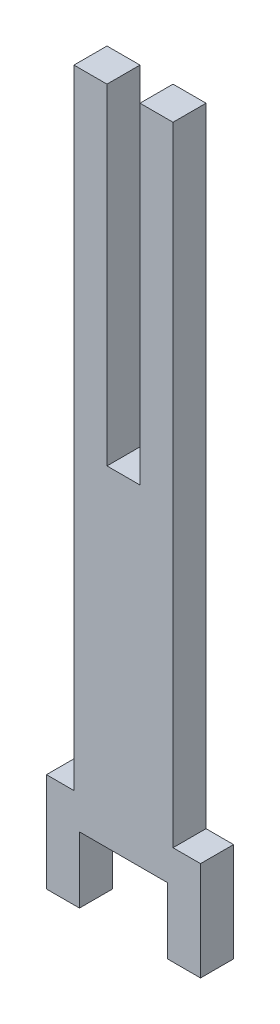
SolidWorks part; units mm, degrees
ref_plane "Front Plane" through (0, 0, 0) normal (0, 0, 1) x (1, 0, 0)
ref_plane "Top Plane" through (0, 0, 0) normal (0, 1, 0) x (1, 0, 0)
ref_plane "Right Plane" through (0, 0, 0) normal (1, 0, 0) x (0, 0, -1)
sketch "스케치1" plane through (0, 0, 0) normal (0, 0, 1) x (1, 0, 0)
  line L0 (0, 0) -> (0, -27.044) construction
  line L1 (-7, -33.044) -> (7, -33.044) construction
  line L2 (-7, -33.044) -> (-7, 33.044) construction
  line L3 (-7, 33.044) -> (7, 33.044) construction
  line L4 (7, -33.044) -> (7, 33.044) construction
  line L5 (-7, -33.044) -> (7, 33.044) construction
  line L6 (-7, 33.044) -> (7, -33.044) construction
  line L7 (-4, -33.044) -> (4, -33.044) construction
  line L8 (-4, -33.044) -> (-4, -27.044)
  line L9 (-4, -27.044) -> (4, -27.044)
  line L10 (4, -33.044) -> (4, -27.044)
  line L11 (-4, -33.044) -> (4, -27.044) construction
  line L12 (-4, -27.044) -> (4, -33.044) construction
  line L13 (4.5, -24.044) -> (-4.5, -24.044) construction
  line L14 (7, -24.044) -> (4.5, -24.044)
  line L15 (7, -24.044) -> (7, 33.044) construction
  line L16 (7, 33.044) -> (4.5, 33.044) construction
  line L17 (4.5, -24.044) -> (4.5, 33.044) construction
  line L18 (7, -24.044) -> (4.5, 33.044) construction
  line L19 (7, 33.044) -> (4.5, -24.044) construction
  line L20 (-4.5, 33.044) -> (-7, 33.044) construction
  line L21 (-4.5, 33.044) -> (-4.5, -24.044) construction
  line L22 (-4.5, -24.044) -> (-7, -24.044)
  line L23 (-7, 33.044) -> (-7, -24.044) construction
  line L24 (-4.5, 33.044) -> (-7, -24.044) construction
  line L25 (-4.5, -24.044) -> (-7, 33.044) construction
  line L26 (4, -33.044) -> (7, -33.044)
  line L27 (-1.5, 24.044) -> (1.5, 24.044) construction
  line L28 (-1.5, 24.044) -> (-1.5, -24.044) construction
  line L29 (-1.5, -24.044) -> (1.5, -24.044) construction
  line L30 (1.5, 24.044) -> (1.5, -24.044) construction
  line L31 (-1.5, 24.044) -> (1.5, -24.044) construction
  line L32 (-1.5, -24.044) -> (1.5, 24.044) construction
  line L33 (7, -33.044) -> (7, -24.044)
  line L34 (-7, -24.044) -> (-7, -33.044)
  line L35 (-7, -33.044) -> (-4, -33.044)
  line L36 (-4.5, 33.044) -> (-7, 33.044) construction
  line L37 (-7, 33.044) -> (-7, -33.044)
  line L38 (4.5, 33.044) -> (7, 33.044) construction
  line L39 (-4.5, -24.044) -> (-4.5, 33.044)
  line L40 (4.5, 33.044) -> (4.5, -24.044)
  line L41 (-4.5, 33.044) -> (4.5, 33.044)
  point P0 (0, 0)
  point P10 (0, -30.044)
  point P16 (5.75, 4.5)
  point P20 (-5.75, 4.5)
  dimension "D1" = 66.088
  dimension "D2" = 3
  dimension "D3" = 8
  dimension "D4" = 6
  dimension "D5" = 3
  dimension "D6" = 3
  dimension "D7" = 3
extrude "보스-돌출1" add sketch "스케치1" along normal blind 3 contours L41 L39 L22 L34 L35 L8 L9 L10 L26 L33 L14 L40
sketch "스케치2" plane through (0, 0, 3) normal (0, 0, 1) x (1, 0, 0)
  line L0 (0, 33.044) -> (0, -27.044) construction
  line L1 (-4.5, 33.044) -> (4.5, 33.044) construction
  line L2 (-4, -27.044) -> (4, -27.044) construction
  line L4 (-1.5, 33.044) -> (1.5, 33.044)
  line L5 (-1.5, 33.044) -> (-1.5, 3)
  line L6 (-1.5, 3) -> (1.5, 3)
  line L7 (1.5, 33.044) -> (1.5, 3)
  line L8 (-1.5, 33.044) -> (1.5, 3) construction
  line L9 (-1.5, 3) -> (1.5, 33.044) construction
  point P6 (0, 3)
  point P7 (0, 18.022)
  dimension "D1" = 3
extrude "컷-돌출1" cut sketch "스케치2" against normal up to surface (3 mm away) up to face at (0, -18.0293, 0)
